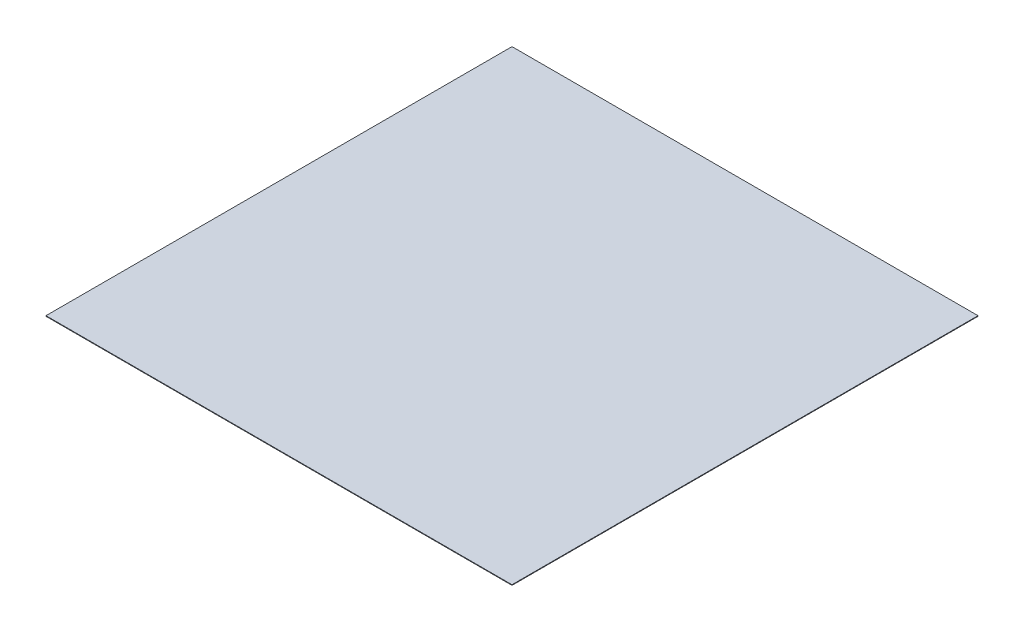
SolidWorks part; units mm, degrees
ref_plane "前视基准面" through (0, 0, 0) normal (0, 0, 1) x (1, 0, 0)
ref_plane "上视基准面" through (0, 0, 0) normal (0, 1, 0) x (1, 0, 0)
ref_plane "右视基准面" through (0, 0, 0) normal (1, 0, 0) x (0, 0, -1)
sketch "草图1" plane through (0, 0, 0) normal (0, 1, 0) x (1, 0, 0)
  line L1 (-400, -400) -> (400, -400)
  line L2 (-400, -400) -> (-400, 400)
  line L3 (-400, 400) -> (400, 400)
  line L4 (400, -400) -> (400, 400)
  line L5 (-400, -400) -> (400, 400) construction
  line L6 (-400, 400) -> (400, -400) construction
  point P0 (0, 0)
  dimension "D1" = 800
  dimension "D2" = 800
extrude "凸台-拉伸1" add sketch "草图1" along normal blind 1
